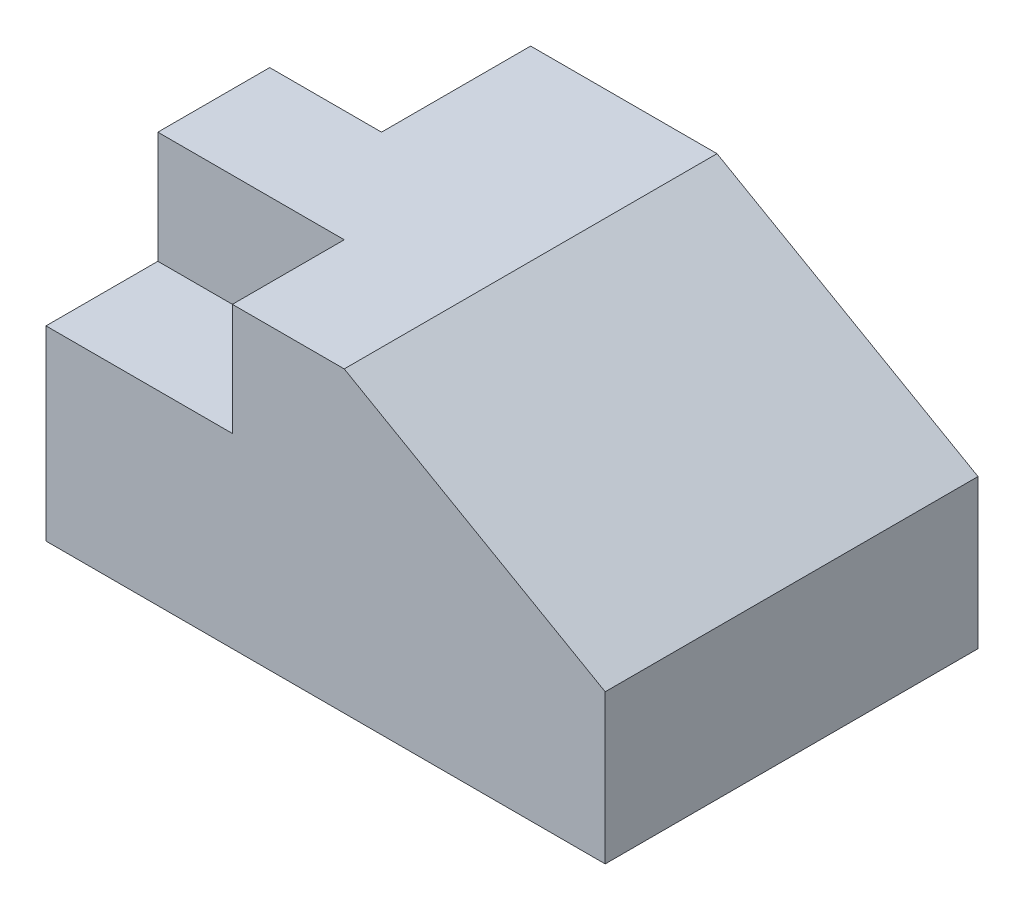
SolidWorks part; units mm, degrees
ref_plane "Front Plane" through (0, 0, 0) normal (0, 0, 1) x (1, 0, 0)
ref_plane "Top Plane" through (0, 0, 0) normal (0, 1, 0) x (1, 0, 0)
ref_plane "Right Plane" through (0, 0, 0) normal (1, 0, 0) x (0, 0, -1)
sketch "Sketch1" plane through (0, 0, 0) normal (0, 0, 1) x (1, 0, 0)
  line L0 (0, 0) -> (150, 0)
  line L1 (150, 0) -> (150, 40)
  line L2 (150, 40) -> (80, 80)
  line L3 (80, 80) -> (0, 80)
  line L4 (0, 80) -> (0, 0)
  dimension "D1" = 150
  dimension "D2" = 80
  dimension "D3" = 40
  dimension "D4" = 80
extrude "Boss-Extrude1" add sketch "Sketch1" against normal blind 100
sketch "Sketch2" plane through (0, 0, 0) normal (0, 0, 1) x (1, 0, 0)
  line L1 (0, 80) -> (50, 80)
  line L2 (0, 80) -> (0, 50)
  line L3 (0, 50) -> (50, 50)
  line L4 (50, 80) -> (50, 50)
  dimension "D1" = 50
  dimension "D2" = 30
extrude "Cut-Extrude1" cut sketch "Sketch2" against normal blind 30
sketch "Sketch3" plane through (0, 80, 0) normal (0, 1, 0) x (1, 0, 0)
  line L1 (0, 100) -> (30, 100)
  line L2 (0, 100) -> (0, 60)
  line L3 (0, 60) -> (30, 60)
  line L4 (30, 100) -> (30, 60)
  dimension "D1" = 30
  dimension "D2" = 40
extrude "Cut-Extrude2" cut sketch "Sketch3" against normal through all
